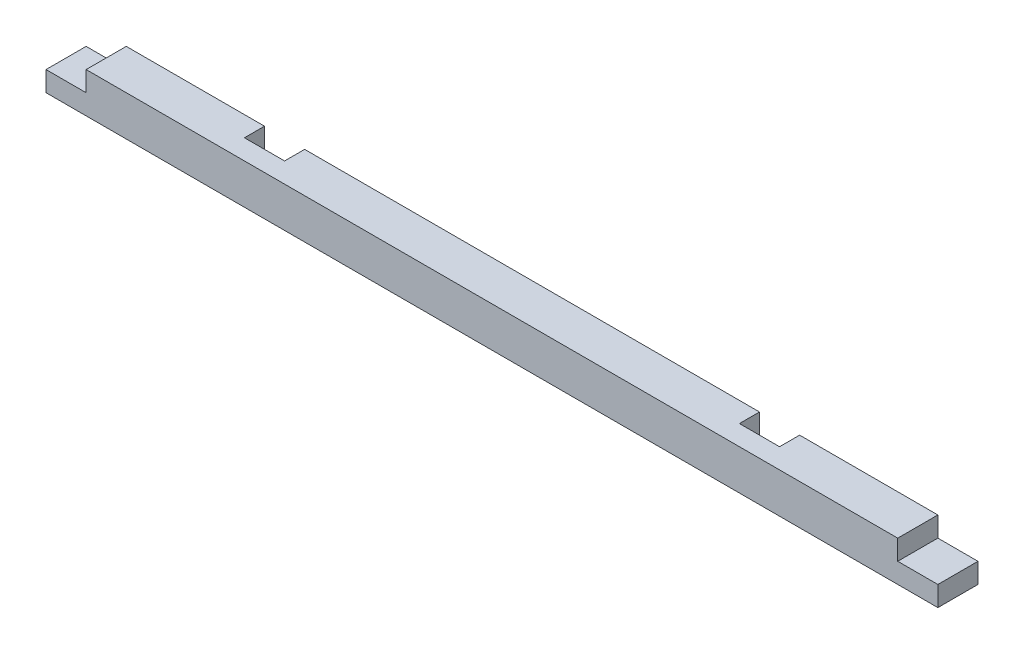
SolidWorks part; units mm, degrees
ref_plane "Front Plane" through (0, 0, 0) normal (0, 0, 1) x (1, 0, 0)
ref_plane "Top Plane" through (0, 0, 0) normal (0, 1, 0) x (1, 0, 0)
ref_plane "Right Plane" through (0, 0, 0) normal (1, 0, 0) x (0, 0, -1)
sketch "Sketch1" plane through (0, 0, 0) normal (1, 0, 0) x (0, 0, -1)
  line L1 (0, 0) -> (90, 0)
  line L2 (0, 0) -> (0, 90)
  line L3 (0, 90) -> (90, 90)
  line L4 (90, 0) -> (90, 90)
  dimension "D1" = 90
  dimension "D2" = 90
extrude "Boss-Extrude1" add sketch "Sketch1" along normal blind 2000
sketch "Sketch2" plane through (0, 90, 0) normal (0, 1, 0) x (1, 0, 0)
  line L0 (2000, 0) -> (0, 0) construction
  line L1 (0, 90) -> (90, 90)
  line L2 (0, 90) -> (0, 0)
  line L3 (0, 0) -> (90, 0)
  line L4 (90, 90) -> (90, 0)
  line L6 (2000, 90) -> (1910, 90)
  line L7 (2000, 90) -> (2000, 0)
  line L8 (2000, 0) -> (1910, 0)
  line L9 (1910, 90) -> (1910, 0)
  dimension "D1" = 90
  dimension "D2" = 90
  dimension "D3" = 90
extrude "Cut-Extrude1" cut sketch "Sketch2" against normal blind 45
sketch "Sketch3" plane through (0, 0, -90) normal (0, 0, -1) x (-1, 0, 0)
  line L0 (-1910, 90) -> (-90, 90) construction
  line L1 (-1600, 90) -> (-1510, 90)
  line L2 (-1600, 90) -> (-1600, 0)
  line L3 (-1600, 0) -> (-1510, 0)
  line L4 (-1510, 90) -> (-1510, 0)
  line L5 (-2000, 0) -> (0, 0) construction
  line L6 (-2000, 0) -> (-2000, 45) construction
  line L7 (0, 0) -> (0, 45) construction
  line L8 (-400, 90) -> (-490, 90)
  line L9 (-400, 90) -> (-400, 0)
  line L10 (-400, 0) -> (-490, 0)
  line L11 (-490, 90) -> (-490, 0)
  dimension "D1" = 90
  dimension "D2" = 400
  dimension "D3" = 90
  dimension "D4" = 400
extrude "Cut-Extrude2" cut sketch "Sketch3" against normal blind 45
